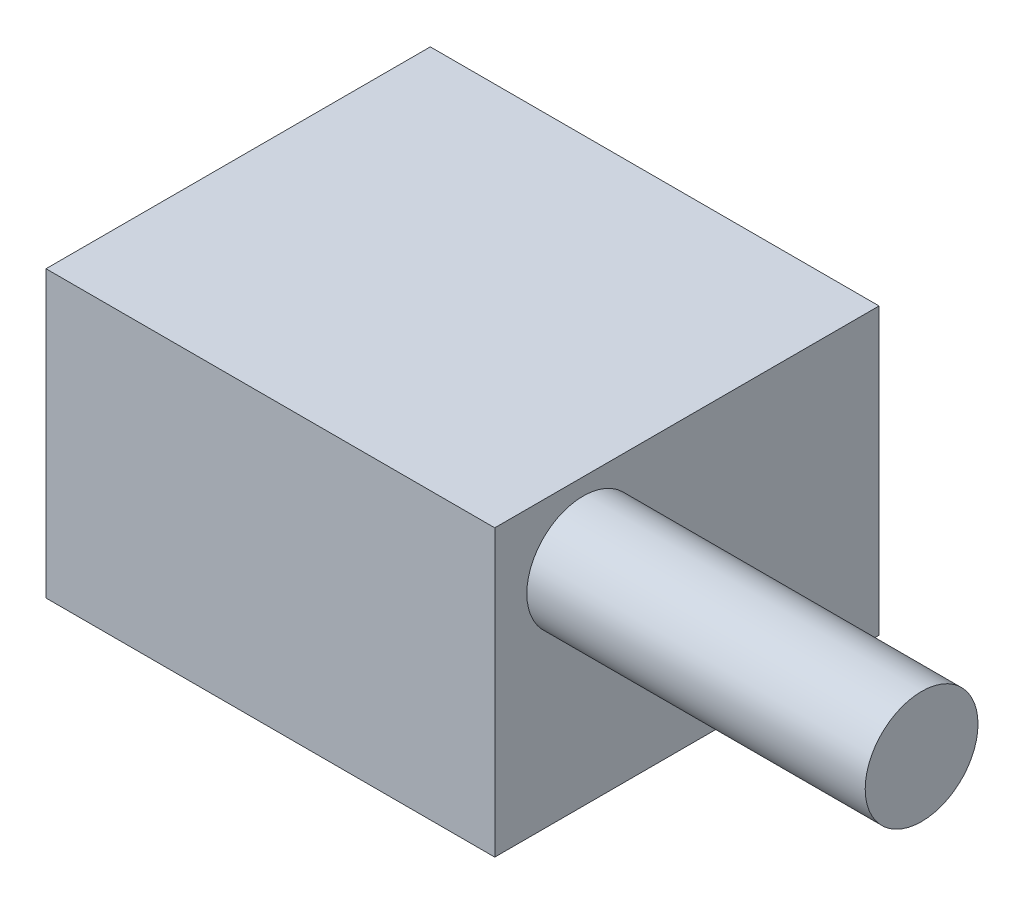
SolidWorks part; units mm, degrees
ref_plane "Front Plane" through (0, 0, 0) normal (0, 0, 1) x (1, 0, 0)
ref_plane "Top Plane" through (0, 0, 0) normal (0, 1, 0) x (1, 0, 0)
ref_plane "Right Plane" through (0, 0, 0) normal (1, 0, 0) x (0, 0, -1)
sketch "Sketch1" plane through (0, 0, 0) normal (0, 1, 0) x (1, 0, 0)
  line L1 (-35.3695, 30.2895) -> (35.3695, 30.2895)
  line L2 (-35.3695, 30.2895) -> (-35.3695, -30.2895)
  line L3 (-35.3695, -30.2895) -> (35.3695, -30.2895)
  line L4 (35.3695, 30.2895) -> (35.3695, -30.2895)
  line L5 (-35.3695, 30.2895) -> (35.3695, -30.2895) construction
  line L6 (-35.3695, -30.2895) -> (35.3695, 30.2895) construction
  point P0 (0, 0)
  dimension "D1" = 70.739
  dimension "D2" = 60.579
extrude "Boss-Extrude1" add sketch "Sketch1" along normal blind 44.958
sketch "Sketch2" plane through (35.3695, 0, 0) normal (1, 0, 0) x (0, 0, -1)
  circle A0 centre (-16.3449, 33.4417) radius 8.89
  point P2 (-16.3449, 33.4417)
  dimension "D1" = 17.78
extrude "Boss-Extrude2" add sketch "Sketch2" along normal blind 53.34
